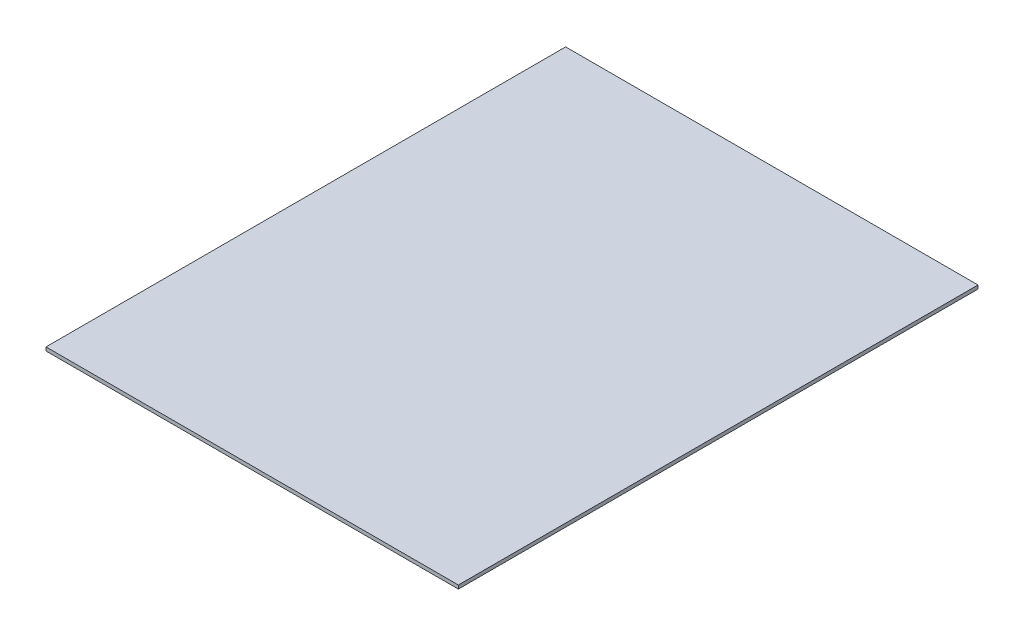
SolidWorks part; units mm, degrees
ref_plane "Front Plane" through (0, 0, 0) normal (0, 0, 1) x (1, 0, 0)
ref_plane "Top Plane" through (0, 0, 0) normal (0, 1, 0) x (1, 0, 0)
ref_plane "Right Plane" through (0, 0, 0) normal (1, 0, 0) x (0, 0, -1)
sketch "Sketch1" plane through (0, 0, 0) normal (0, 1, 0) x (1, 0, 0)
  line L1 (0, 0) -> (-346, 0)
  line L2 (0, 0) -> (0, 436)
  line L3 (0, 436) -> (-346, 436)
  line L4 (-346, 0) -> (-346, 436)
  dimension "D1" = 346
  dimension "D2" = 436
extrude "Boss-Extrude1" add sketch "Sketch1" along normal blind 3
